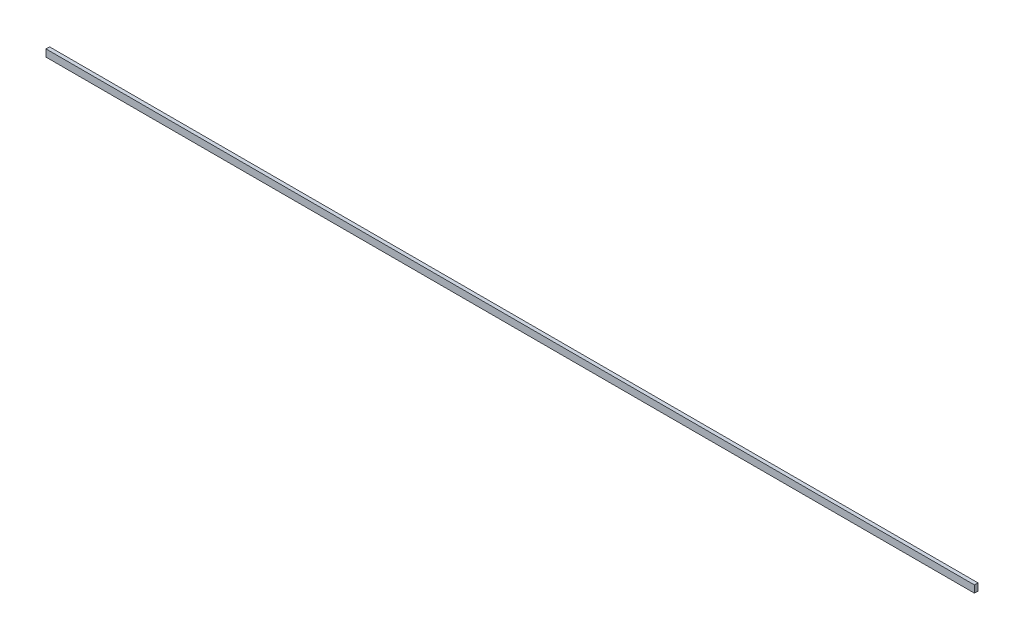
SolidWorks part; units mm, degrees
ref_plane "Front Plane" through (0, 0, 0) normal (0, 0, 1) x (1, 0, 0)
ref_plane "Top Plane" through (0, 0, 0) normal (0, 1, 0) x (1, 0, 0)
ref_plane "Right Plane" through (0, 0, 0) normal (1, 0, 0) x (0, 0, -1)
sketch "Sketch1" plane through (0, 0, 0) normal (0, 1, 0) x (1, 0, 0)
  line L1 (0, 0) -> (1300, 0)
  line L2 (0, 0) -> (0, -5)
  line L3 (0, -5) -> (1300, -5)
  line L4 (1300, 0) -> (1300, -5)
  dimension "D1" = 5
  dimension "D2" = 1300
extrude "Boss-Extrude1" add sketch "Sketch1" along normal blind 10 contours L3 L4 L1 L2
